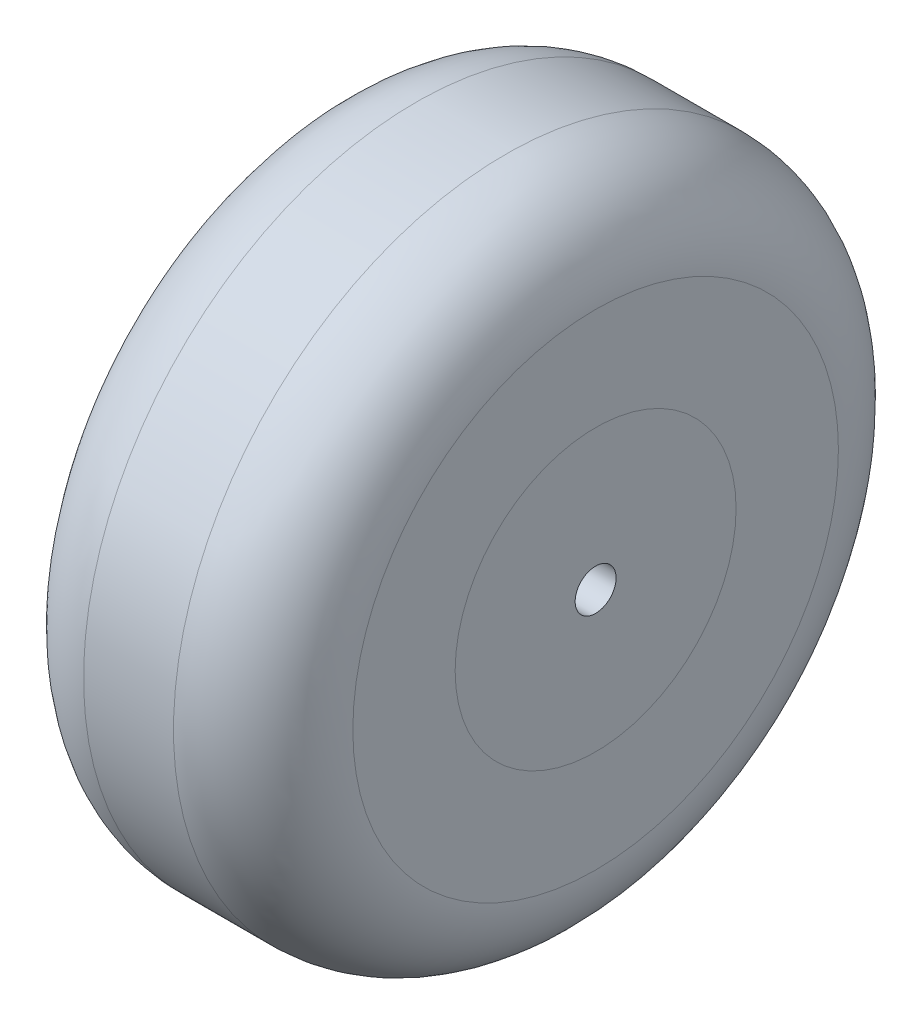
SolidWorks part; units mm, degrees
ref_plane "Front Plane" through (0, 0, 0) normal (0, 0, 1) x (1, 0, 0)
ref_plane "Top Plane" through (0, 0, 0) normal (0, 1, 0) x (1, 0, 0)
ref_plane "Right Plane" through (0, 0, 0) normal (1, 0, 0) x (0, 0, -1)
sketch "Sketch1" plane through (0, 0, 0) normal (1, 0, 0) x (0, 0, -1)
  circle A0 centre (0, 0) radius 36.068
  dimension "D1" = 72.136
extrude "Boss-Extrude1" add sketch "Sketch1" along normal blind 29.21
fillet "Fillet1" radius 9.7282 1 edges at (29.21, 0, -36.068)
fillet "Fillet2" radius 9.7282 1 edges at (0, 0, -36.068)
sketch "Sketch2" plane through (29.21, 0, 0) normal (1, 0, 0) x (0, 0, -1)
  circle A0 centre (0, 0) radius 15.24
extrude "Cut-Extrude1" cut sketch "Sketch2" against normal through all
sketch "Sketch3" plane through (29.21, 0, 0) normal (1, 0, 0) x (0, 0, -1)
  circle A0 centre (0, 0) radius 15.24
  dimension "D1" = 30.48
extrude "Boss-Extrude2" add sketch "Sketch3" against normal blind 29.21 separate body
sketch "Sketch4" plane through (29.21, 0, 0) normal (1, 0, 0) x (0, 0, -1)
  circle A0 centre (0, 0) radius 2.2225
  dimension "D1" = 4.445
extrude "Cut-Extrude2" cut sketch "Sketch4" against normal blind 29.21
sketch "Sketch5" [suppressed] plane through (29.21, 0, 0) normal (1, 0, 0) x (0, 0, -1)
  circle A0 centre (0, 0) radius 3.175
